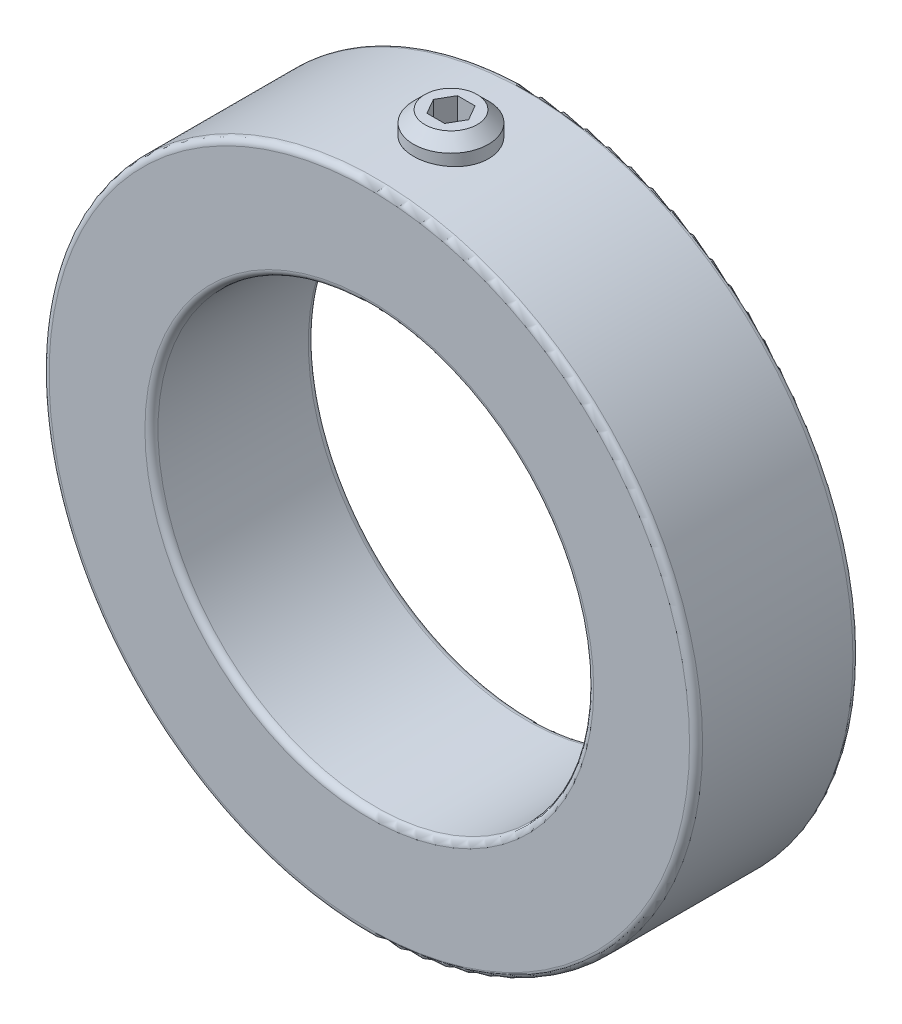
SolidWorks part; units mm, degrees
ref_plane "Front Plane" through (0, 0, 0) normal (0, 0, 1) x (1, 0, 0)
ref_plane "Top Plane" through (0, 0, 0) normal (0, 1, 0) x (1, 0, 0)
ref_plane "Right Plane" through (0, 0, 0) normal (1, 0, 0) x (0, 0, -1)
sketch "Sketch1" plane through (0, 0, 0) normal (0, 0, 1) x (1, 0, 0)
  circle A0 centre (0, 0) radius 9.525
  circle A1 centre (0, 0) radius 6.35
  point P4 (9.525, 0)
  dimension "Bore Dia" = 12.7
  dimension "OD" = 19.05
extrude "Extrude1" add sketch "Sketch1" along normal mid plane 4.7625
sketch "Sketch2" plane through (41.275, 0, 0) normal (0, -1, 0) x (0, 0, -1)
  line L0 (2.3812, -41.275) -> (-2.3813, -41.275) construction
  line L1 (-2.3813, -31.75) -> (-2.3813, -50.8) construction
  line L2 (2.3813, -50.8) -> (2.3813, -31.75) construction
  circle A0 centre (0, -41.275) radius 1.0922
  point P7 (0, -42.3672)
  dimension "Set Screw Dia" = 2.1844
extrude "Cut-Extrude1" cut sketch "Sketch2" against normal through all
fillet "Fillet1" radius 0.1905 4 edges at (6.35, 0, -2.3813) (6.35, 0, 2.3813) (9.525, 0, -2.3813) (9.525, 0, 2.3813)
sketch "Sketch3" plane through (0, 0, 0) normal (0, 0, 1) x (1, 0, 0)
  line L0 (-0.7614, 6.35) -> (-0.397, 6.35)
  line L1 (0, 6.747) -> (-0.397, 6.35)
  line L2 (0, 6.747) -> (0, 10.16)
  line L3 (0, 10.16) -> (-0.7614, 10.16)
  line L4 (-1.0922, 6.6808) -> (-1.0922, 9.8292)
  line L5 (0, 6.35) -> (0, 0) construction
  line L6 (-1.0922, 6.6808) -> (-1.0922, 6.35) construction
  line L7 (-1.0922, 6.35) -> (-0.7614, 6.35) construction
  line L8 (-1.0922, 9.8292) -> (-1.0922, 10.16) construction
  line L9 (-0.7614, 6.35) -> (-1.0922, 6.6808)
  line L10 (-1.0922, 9.8292) -> (-0.7614, 10.16)
  line L11 (-1.0922, 10.16) -> (-0.7614, 10.16) construction
  line L12 (-0.397, 6.35) -> (0, 6.35) construction
  line L13 (0, 6.35) -> (0, 6.747) construction
  circle A1 centre (0, 0) radius 6.35 construction
  dimension "Screw Length" = 3.81
  dimension "D2" = 0.3308
  dimension "D1" = 0.397
revolve "Revolve1" add sketch "Sketch3" angle 360 about L5
sketch "Sketch4" plane through (3.3734, 10.16, 0) normal (0, -1, 0) x (0, 0, -1)
  line L1 (0, -2.8602) -> (-0.4445, -3.1168)
  line L2 (-0.4445, -3.1168) -> (-0.4445, -3.6301)
  line L3 (-0.4445, -3.6301) -> (0, -3.8867)
  line L4 (0, -3.8867) -> (0.4445, -3.6301)
  line L5 (0.4445, -3.6301) -> (0.4445, -3.1168)
  line L6 (0.4445, -3.1168) -> (0, -2.8602)
  circle A0 centre (0, -3.3734) radius 0.4445 construction
  circle A1 centre (0, -3.3734) radius 0.5133 construction
  dimension "Hex Size" = 0.889
extrude "Cut-Extrude2" cut sketch "Sketch4" along normal blind 0.889
equation "\"D1@Fillet1\" = \"OD@Sketch1\"*.01"
equation "\"D1@Cut-Extrude2\" = \"Hex Size@Sketch4\""
equation "\"D2@Sketch3\" =(\"Set Screw Dia@Sketch2\"-\"D1@Sketch4\")/3.5"
equation "\"D1@Sketch3\" = \"D2@Sketch3\"*1.2"
